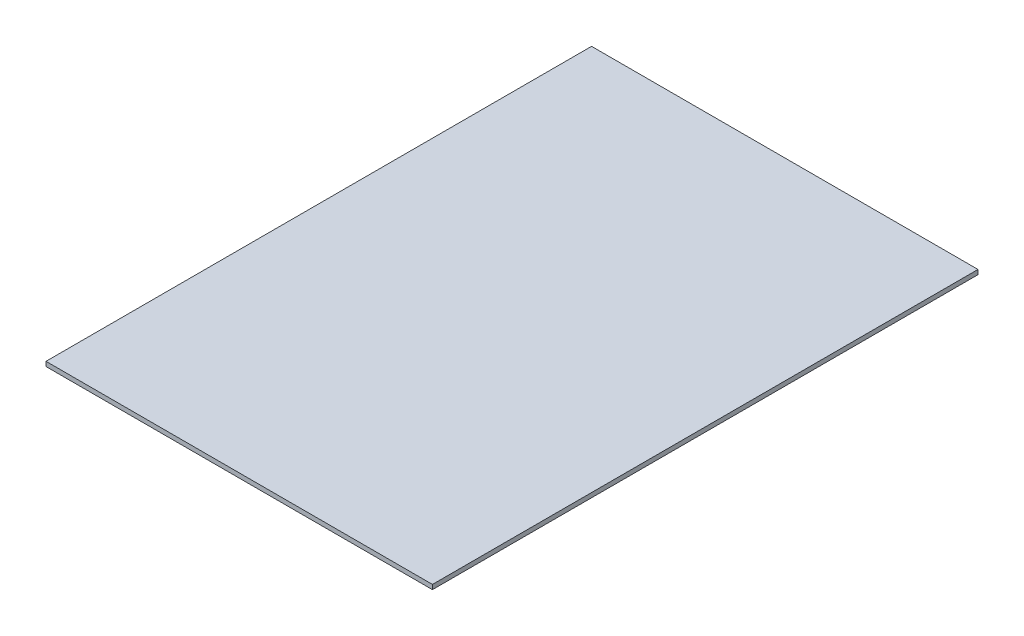
SolidWorks part; units mm, degrees
ref_plane "Спереди" through (0, 0, 0) normal (0, 0, 1) x (1, 0, 0)
ref_plane "Сверху" through (0, 0, 0) normal (0, 1, 0) x (1, 0, 0)
ref_plane "Справа" through (0, 0, 0) normal (1, 0, 0) x (0, 0, -1)
other "Configuration Table"
sketch "Эскиз1" plane through (0, 0, 0) normal (0, 1, 0) x (1, 0, 0)
  line L1 (-42.5, -60) -> (42.5, -60)
  line L2 (-42.5, -60) -> (-42.5, 60)
  line L3 (-42.5, 60) -> (42.5, 60)
  line L4 (42.5, -60) -> (42.5, 60)
  line L5 (-42.5, -60) -> (42.5, 60) construction
  line L6 (-42.5, 60) -> (42.5, -60) construction
  point P0 (0, 0)
  dimension "D1" = 85
  dimension "D2" = 120
extrude "Бобышка-Вытянуть1" add sketch "Эскиз1" along normal blind 1
